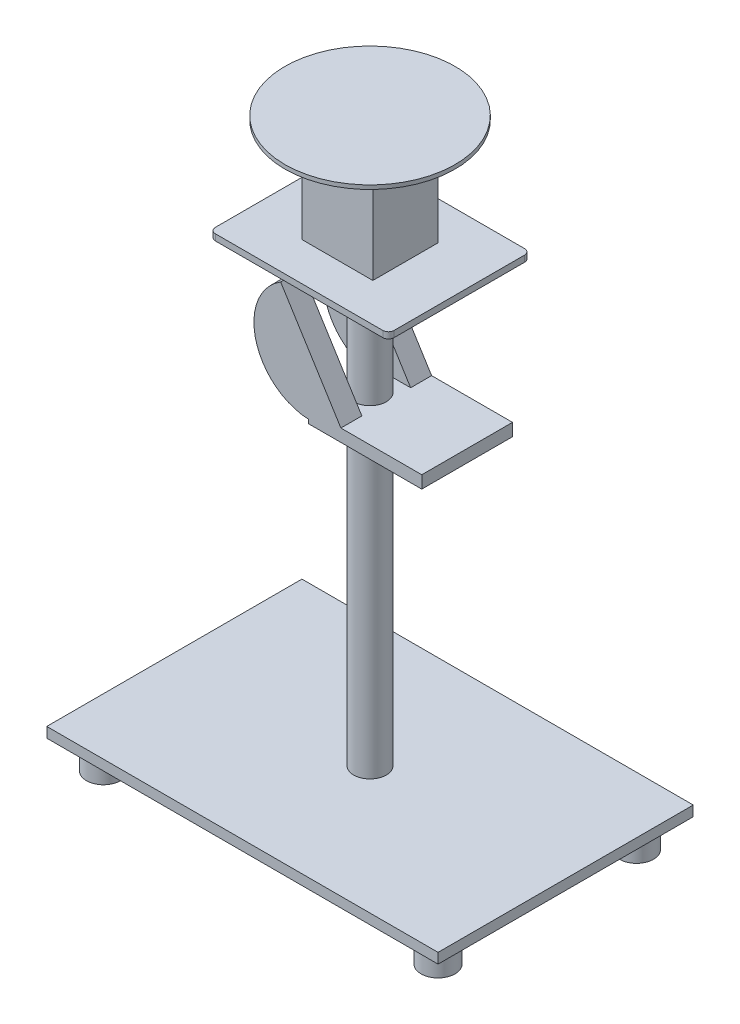
SolidWorks part; units mm, degrees
ref_plane "Front Plane" through (0, 0, 0) normal (0, 0, 1) x (1, 0, 0)
ref_plane "Top Plane" through (0, 0, 0) normal (0, 1, 0) x (1, 0, 0)
ref_plane "Right Plane" through (0, 0, 0) normal (1, 0, 0) x (0, 0, -1)
sketch "Sketch2" plane through (0, 0, 0) normal (0, 1, 0) x (1, 0, 0)
  circle A0 centre (0, 0) radius 150.0263
extrude "Boss-Extrude1" add sketch "Sketch2" against normal blind 7
sketch "Sketch3" plane through (0, -7, 0) normal (0, -1, 0) x (1, 0, 0)
  line L1 (62.5, -57.5) -> (-62.5, -57.5)
  line L2 (62.5, -57.5) -> (62.5, 57.5)
  line L3 (62.5, 57.5) -> (-62.5, 57.5)
  line L4 (-62.5, -57.5) -> (-62.5, 57.5)
  line L5 (62.5, -57.5) -> (-62.5, 57.5) construction
  line L6 (62.5, 57.5) -> (-62.5, -57.5) construction
  point P0 (0, 0)
  dimension "D1" = 125
  dimension "D2" = 115
extrude "Boss-Extrude2" add sketch "Sketch3" along normal blind 185
sketch "Sketch4" plane through (0, -192, 0) normal (0, -1, 0) x (1, 0, 0)
  line L1 (157.5, -125) -> (-157.5, -125)
  line L2 (157.5, -125) -> (157.5, 125)
  line L3 (157.5, 125) -> (-157.5, 125)
  line L4 (-157.5, -125) -> (-157.5, 125)
  line L5 (157.5, -125) -> (-157.5, 125) construction
  line L6 (157.5, 125) -> (-157.5, -125) construction
  point P0 (0, 0)
  dimension "D1" = 315
  dimension "D2" = 250
extrude "Boss-Extrude3" add sketch "Sketch4" along normal blind 11
sketch "Sketch5" plane through (0, -203, 0) normal (0, -1, 0) x (1, 0, 0)
  circle A0 centre (0, 0) radius 28.6624
extrude "Boss-Extrude4" add sketch "Sketch5" along normal blind 790
sketch "Sketch6" plane through (0, -993, 0) normal (0, -1, 0) x (1, 0, 0)
  line L1 (345, -225) -> (-345, -225)
  line L2 (345, -225) -> (345, 225)
  line L3 (345, 225) -> (-345, 225)
  line L4 (-345, -225) -> (-345, 225)
  line L5 (345, -225) -> (-345, 225) construction
  line L6 (345, 225) -> (-345, -225) construction
  point P0 (0, 0)
  dimension "D1" = 690
  dimension "D2" = 450
extrude "Boss-Extrude5" add sketch "Sketch6" along normal blind 18
sketch "Sketch7" plane through (0, -1011, 0) normal (0, -1, 0) x (1, 0, 0)
  line L0 (-345, 175) -> (345, 175) construction
  line L1 (-345, 225) -> (-345, -225) construction
  line L2 (345, -225) -> (345, 225) construction
  line L3 (-295, 225) -> (-295, -225) construction
  line L4 (345, 225) -> (-345, 225) construction
  line L5 (-345, -225) -> (345, -225) construction
  line L6 (-345, -175) -> (345, -175) construction
  line L7 (295, 225) -> (295, -225) construction
  circle A0 centre (-295, 175) radius 29.9714
  circle A1 centre (-295, -175) radius 29.9714
  circle A2 centre (295, 175) radius 29.9714
  circle A3 centre (295, -175) radius 29.9714
  dimension "D1" = 50
  dimension "D2" = 50
  dimension "D3" = 50
  dimension "D4" = 50
extrude "Boss-Extrude6" add sketch "Sketch7" along normal blind 50
ref_plane "Plane1" through (0, -423, 0) normal (0, -1, 0) x (-1, 0, 0)
sketch "Sketch11" plane through (0, -423, 0) normal (0, -1, 0) x (-1, 0, 0)
  line L0 (0, 0) -> (28.7098, 0) construction
  line L1 (28.7098, 0) -> (28.7098, -160) construction
  line L2 (28.7098, 0) -> (28.7098, 160) construction
  line L3 (28.7098, 0) -> (28.7098, -80)
  line L4 (28.7098, 0) -> (28.7098, 80)
  line L5 (28.7098, -80) -> (-171.2902, -80)
  line L6 (-171.2902, -80) -> (-171.2902, 80)
  line L7 (-171.2902, 80) -> (28.7098, 80)
  dimension "D1" = 80
  dimension "D2" = 80
  dimension "D3" = 200
extrude "Boss-Extrude7" add sketch "Sketch11" along normal blind 22
sketch "Sketch12" plane through (0, 0, 80) normal (0, 0, 1) x (1, 0, 0)
  line L0 (-77.568, -253) -> (28.6624, -423)
  line L2 (-258.56, -253) -> (249.9413, -253) construction
  arc A0 (-77.568, -253) -> (28.6624, -423) centre (-24.4528, -338) ccw
extrude "Boss-Extrude8" add sketch "Sketch12" against normal blind 37
mirror "Mirror1" about plane through (0, 0, 0) normal (0, 0, 1) of "Boss-Extrude8"
fillet "Fillet1" radius 10 4 edges at (-157.5, -197.5, 125) (-157.5, -197.5, -125) (157.5, -197.5, -125) (157.5, -197.5, 125)
